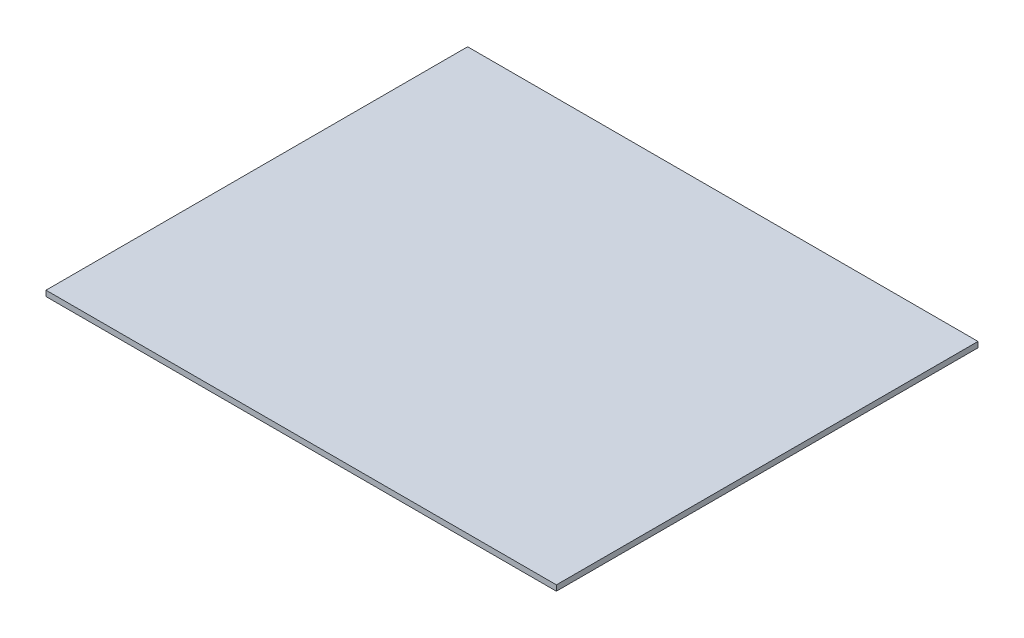
SolidWorks part; units mm, degrees
ref_plane "前视基准面" through (0, 0, 0) normal (0, 0, 1) x (1, 0, 0)
ref_plane "上视基准面" through (0, 0, 0) normal (0, 1, 0) x (1, 0, 0)
ref_plane "右视基准面" through (0, 0, 0) normal (1, 0, 0) x (0, 0, -1)
sketch "草图1" plane through (0, 0, 0) normal (0, 0, 1) x (1, 0, 0)
  line L1 (-230, -5) -> (230, -5)
  line L2 (-230, -5) -> (-230, 0)
  line L3 (-230, 0) -> (230, 0)
  line L4 (230, -5) -> (230, 0)
  line L5 (-230, -5) -> (230, 0) construction
  line L6 (-230, 0) -> (230, -5) construction
  point P0 (0, -2.5)
  dimension "D1" = 230
  dimension "D2" = 2.5
extrude "地面基准_顶面Y0" add sketch "草图1" along normal blind 380 from offset 280
